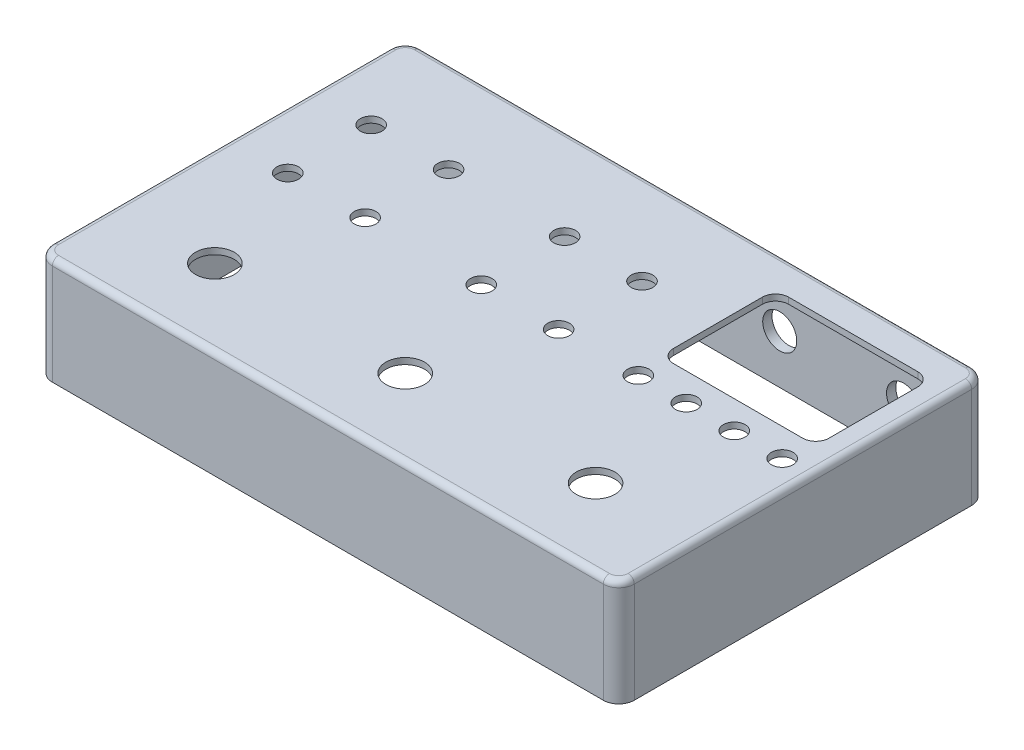
SolidWorks part; units mm, degrees
ref_plane "前视基准面" through (0, 0, 0) normal (0, 0, 1) x (1, 0, 0)
ref_plane "上视基准面" through (0, 0, 0) normal (0, 1, 0) x (1, 0, 0)
ref_plane "右视基准面" through (0, 0, 0) normal (1, 0, 0) x (0, 0, -1)
sketch "草图1" plane through (0, 0, 0) normal (0, 1, 0) x (1, 0, 0)
  line L0 (-67.19, 26.9473) -> (101.81, 26.9473) construction
  line L1 (-86.19, 56.9473) -> (101.81, 56.9473)
  line L2 (-86.19, 56.9473) -> (-86.19, -62.0527)
  line L3 (-86.19, -62.0527) -> (101.81, -62.0527)
  line L4 (101.81, 56.9473) -> (101.81, -62.0527)
  line L5 (-86.19, 26.9473) -> (-67.19, 26.9473) construction
  line L6 (-86.19, 0) -> (101.81, 0) construction
  line L7 (-86.19, -37.0527) -> (101.81, -37.0527) construction
  line L9 (48.445, 45.9473) -> (90.175, 45.9473)
  line L10 (44.445, 41.9473) -> (44.445, 13.2473)
  line L11 (48.445, 9.2473) -> (90.175, 9.2473)
  line L12 (94.175, 41.9473) -> (94.175, 13.2473)
  circle A0 centre (-67.19, 26.9473) radius 3.5
  circle A1 centre (-42.19, 26.9473) radius 3.5
  circle A2 centre (-67.19, 0) radius 3.5
  circle A3 centre (-42.19, 0) radius 3.5
  circle A4 centre (-4.69, 26.9473) radius 3.5
  circle A5 centre (20.31, 26.9473) radius 3.5
  circle A6 centre (-4.69, 0) radius 3.5
  circle A7 centre (20.31, 0) radius 3.5
  circle A8 centre (46.06, 0) radius 3.5
  circle A9 centre (61.56, 0) radius 3.5
  circle A10 centre (77.06, 0) radius 3.5
  circle A11 centre (92.56, 0) radius 3.5
  circle A12 centre (-53.69, -37.0527) radius 6.25
  circle A13 centre (7.81, -37.0527) radius 6.25
  circle A14 centre (69.31, -37.0527) radius 6.25
  arc A15 (90.175, 45.9473) -> (94.175, 41.9473) centre (90.175, 41.9473) cw
  arc A16 (48.445, 45.9473) -> (44.445, 41.9473) centre (48.445, 41.9473) ccw
  arc A17 (90.175, 9.2473) -> (94.175, 13.2473) centre (90.175, 13.2473) ccw
  arc A18 (44.445, 13.2473) -> (48.445, 9.2473) centre (48.445, 13.2473) ccw
  point P43 (69.31, 45.9473)
  point P49 (94.175, 45.9473)
  point P52 (44.445, 45.9473)
  point P55 (94.175, 9.2473)
  dimension "D3" = 30
  dimension "D12" = 7
  dimension "D16" = 12.5
  dimension "D19" = 49.73
  dimension "D23" = 4
  dimension "D1" = 188
  dimension "D2" = 119
  dimension "D4" = 19
  dimension "D5" = 25
  dimension "D6" = 25
  dimension "D7" = 37.5
  dimension "D8" = 9.25
  dimension "D9" = 15.5
  dimension "D10" = 15.5
  dimension "D11" = 15.5
  dimension "D13" = 32.5
  dimension "D14" = 61.5
  dimension "D15" = 61.5
  dimension "D17" = 25.75
  dimension "D18" = 19
  dimension "D20" = 36.7
  dimension "D21" = 11
  dimension "D22" = 25
extrude "凸台-拉伸1" add sketch "草图1" along normal blind 34.5
sketch "草图3" plane through (0, 0, 0) normal (0, -1, 0) x (1, 0, 0)
  line L1 (98.81, -53.9473) -> (-83.19, -53.9473)
  line L2 (98.81, -53.9473) -> (98.81, 59.0527)
  line L3 (98.81, 59.0527) -> (-83.19, 59.0527)
  line L4 (-86.19, 62.0527) -> (-86.19, -56.9473)
  line L5 (-86.19, -56.9473) -> (101.81, -56.9473)
  line L6 (101.81, -56.9473) -> (101.81, 62.0527)
  line L7 (101.81, 62.0527) -> (-86.19, 62.0527)
  line L8 (-86.19, 62.0527) -> (-86.19, -56.9473)
  line L9 (-86.19, -56.9473) -> (101.81, -56.9473)
  line L10 (101.81, -56.9473) -> (101.81, 62.0527)
  line L11 (101.81, 62.0527) -> (-86.19, 62.0527)
  line L12 (-83.19, -53.9473) -> (-83.19, 59.0527)
  dimension "D2" = 3
  dimension "D3" = 3
  dimension "D4" = 3
  dimension "D5" = 3
  dimension "D1" = 0
extrude "切除-拉伸2" cut sketch "草图3" against normal offset from surface (31.5 mm away) 3 up to face at (7.81, 34.5, 43.3027)
sketch "草图4" plane through (0, 34.5, 0) normal (0, 1, 0) x (1, 0, 0)
  line L0 (90.175, 45.9473) -> (48.445, 45.9473)
  line L1 (90.175, 45.9473) -> (48.445, 45.9473)
  line L2 (44.445, 41.9473) -> (44.445, 13.2473)
  line L3 (44.445, 41.9473) -> (44.445, 13.2473)
  line L4 (94.175, 13.2473) -> (94.175, 41.9473)
  line L5 (94.175, 13.2473) -> (94.175, 41.9473)
  line L6 (48.445, 9.2473) -> (90.175, 9.2473)
  line L7 (48.445, 9.2473) -> (90.175, 9.2473)
  arc A0 (48.445, 45.9473) -> (44.445, 41.9473) centre (48.445, 41.9473) ccw
  arc A1 (48.445, 45.9473) -> (44.445, 41.9473) centre (48.445, 41.9473) ccw
  arc A2 (44.445, 13.2473) -> (48.445, 9.2473) centre (48.445, 13.2473) ccw
  arc A3 (44.445, 13.2473) -> (48.445, 9.2473) centre (48.445, 13.2473) ccw
  arc A4 (94.175, 41.9473) -> (90.175, 45.9473) centre (90.175, 41.9473) ccw
  arc A5 (94.175, 41.9473) -> (90.175, 45.9473) centre (90.175, 41.9473) ccw
  arc A6 (90.175, 9.2473) -> (94.175, 13.2473) centre (90.175, 13.2473) ccw
  arc A7 (90.175, 9.2473) -> (94.175, 13.2473) centre (90.175, 13.2473) ccw
extrude "切除-拉伸-薄壁1" cut sketch "草图4" against normal blind 3 thin
fillet "圆角1" radius 5 8 edges at (-86.19, 17.25, -56.9473) (-86.19, 17.25, 62.0527) (-83.19, 15.75, 59.0527) (98.81, 15.75, -53.9473) (101.81, 17.25, -56.9473) (101.81, 17.25, 62.0527) (98.81, 15.75, 59.0527) (-83.19, 15.75, -53.9473)
sketch "草图5" plane through (0, 31.5, 0) normal (0, -1, 0) x (1, 0, 0)
  line L0 (93.81, 59.0527) -> (-78.19, 59.0527) construction
  line L1 (-80.69, -51.4473) -> (96.31, -51.4473)
  line L2 (-80.69, -51.4473) -> (-80.69, 56.5527)
  line L3 (-80.69, 56.5527) -> (96.31, 56.5527)
  line L4 (96.31, -51.4473) -> (96.31, 56.5527)
  line L5 (-83.19, -48.9473) -> (-83.19, 54.0527) construction
  line L6 (98.81, -48.9473) -> (98.81, 54.0527) construction
  line L7 (93.81, -53.9473) -> (-78.19, -53.9473) construction
  circle A0 centre (-80.69, -51.4473) radius 3.5
  circle A1 centre (-80.69, 56.5527) radius 3.5
  circle A2 centre (96.31, 56.5527) radius 3.5
  circle A3 centre (96.31, -51.4473) radius 3.5
  arc M34 (-78.19, 59.0527) -> (-83.19, 54.0527) centre (-78.19, 54.0527) ccw
  arc M36 (-83.19, -48.9473) -> (-78.19, -53.9473) centre (-78.19, -48.9473) ccw
  arc M38 (93.81, -53.9473) -> (98.81, -48.9473) centre (93.81, -48.9473) ccw
  arc M40 (98.81, 54.0527) -> (93.81, 59.0527) centre (93.81, 54.0527) ccw
  dimension "D1" = 2.5
  dimension "D5" = 7
  dimension "D2" = 2.5
  dimension "D3" = 2.5
  dimension "D4" = 2.5
extrude "凸台-拉伸2" add sketch "草图5" along normal up to surface (31.5 mm away) contours L3 A1 L2 M34 | L2 A1 L3 | A0 L1 L2 M36 | L1 A0 L2 | L3 A2 L4 | L4 A2 L3 M40 | L4 A3 L1 | A3 L4 L1 M38 up to face at (7.81, 0, 2.5527)
sketch "草图6" plane through (0, 0, 0) normal (0, -1, 0) x (1, 0, 0)
  circle A0 centre (96.31, -51.4473) radius 2.25
  circle A1 centre (96.31, 56.5527) radius 2.25
  circle A2 centre (-80.69, 56.5527) radius 2.25
  circle A3 centre (-80.69, -51.4473) radius 2.25
  dimension "D1" = 4.5
extrude "切除-拉伸3" cut sketch "草图6" against normal blind 20
fillet "圆角2" radius 2 8 edges at (-84.7255, 34.5, 60.5882) (-84.7255, 34.5, -55.4828) (100.3456, 34.5, -55.4828) (100.3456, 34.5, 60.5882) (101.81, 34.5, 2.5527) (7.81, 34.5, -56.9473) (-86.19, 34.5, 2.5527) (7.81, 34.5, 62.0527)
sketch "草图7" plane through (0, 0, -56.9473) normal (0, 0, -1) x (-1, 0, 0)
  line L0 (-96.81, 15.75) -> (81.19, 15.75) construction
  line L3 (-96.81, 32.5) -> (-96.81, 0) construction
  line L4 (81.19, 0) -> (81.19, 32.5) construction
  line L5 (-96.81, 34.5) -> (81.19, 34.5) construction
  line L8 (27.19, 19.25) -> (37.19, 19.25)
  line L9 (27.19, 19.25) -> (27.19, 12.25)
  line L10 (27.19, 12.25) -> (37.19, 12.25)
  line L11 (37.19, 19.25) -> (37.19, 12.25)
  line L12 (23.69, 17.5) -> (40.69, 17.5)
  line L13 (23.69, 17.5) -> (23.69, 14)
  line L14 (23.69, 14) -> (40.69, 14)
  line L15 (40.69, 17.5) -> (40.69, 14)
  circle A0 centre (-7.81, 15.75) radius 5.5
  circle A1 centre (62.19, 15.75) radius 5.5
  circle A3 centre (23.69, 15.75) radius 1.75
  circle A4 centre (40.69, 15.75) radius 1.75
  circle A5 centre (-37.81, 15.75) radius 5.5
  circle A6 centre (-77.81, 15.75) radius 5.5
  circle A7 centre (12.19, 15.75) radius 3
  point P14 (27.19, 15.75)
  point P21 (32.19, 19.25)
  point P22 (-7.81, 15.75)
  point P29 (32.19, 17.5)
  dimension "D2" = 30
  dimension "D5" = 11
  dimension "D6" = 11
  dimension "D7" = 3.5
  dimension "D3" = 3.5
  dimension "D11" = 11
  dimension "D14" = 6
  dimension "D1" = 18.75
  dimension "D4" = 17
  dimension "D8" = 3.5
  dimension "D9" = 7
  dimension "D10" = 40
  dimension "D12" = 30
  dimension "D13" = 40
  dimension "D15" = 20
  dimension "D16" = 10
extrude "切除-拉伸4" cut sketch "草图7" against normal blind 20 contours A1 L0 | A6 L0 | L0 A6 | A5 L0 | L0 A5 | A7 L0 | L8 L11 L10 L9 | A3 | A4
sketch "草图8" plane through (-86.19, 0, 0) normal (-1, 0, 0) x (0, 0, 1)
  line L0 (-56.9473, 0) -> (-56.9473, 32.5) construction
  line L1 (-51.9473, 34.5) -> (57.0527, 34.5) construction
  circle A0 centre (-31.9473, 15.75) radius 5
  dimension "D1" = 25
  dimension "D3" = 10
  dimension "D2" = 18.75
sketch "草图10" plane through (0, 31.5, 0) normal (0, -1, 0) x (1, 0, 0)
  line L4 (98.81, -48.9473) -> (98.81, 54.0527)
  line L5 (93.81, 59.0527) -> (-78.19, 59.0527)
  line L6 (-83.19, 54.0527) -> (-83.19, -48.9473)
  line L7 (-78.19, -53.9473) -> (93.81, -53.9473)
  line L8 (98.81, -48.9473) -> (98.81, 54.0527)
  line L9 (93.81, 59.0527) -> (-78.19, 59.0527)
  line L10 (-83.19, 54.0527) -> (-83.19, -48.9473)
  line L11 (-78.19, -53.9473) -> (93.81, -53.9473)
  arc A12 (98.8098, -48.9975) -> (93.8603, -53.947) centre (96.31, -51.4473) ccw
  arc A13 (98.8098, -48.9975) -> (98.81, -48.9473) centre (93.81, -48.9473) ccw
  arc A14 (98.81, 54.0527) -> (98.8098, 54.103) centre (93.81, 54.0527) ccw
  arc A15 (93.8603, 59.0525) -> (98.8098, 54.103) centre (96.31, 56.5527) ccw
  arc A16 (93.8603, 59.0525) -> (93.81, 59.0527) centre (93.81, 54.0527) ccw
  arc A17 (-78.19, 59.0527) -> (-78.2402, 59.0525) centre (-78.19, 54.0527) ccw
  arc A18 (-83.1897, 54.103) -> (-78.2402, 59.0525) centre (-80.69, 56.5527) ccw
  arc A19 (-83.1897, 54.103) -> (-83.19, 54.0527) centre (-78.19, 54.0527) ccw
  arc A20 (-83.19, -48.9473) -> (-83.1897, -48.9975) centre (-78.19, -48.9473) ccw
  arc A21 (-78.2402, -53.947) -> (-83.1897, -48.9975) centre (-80.69, -51.4473) ccw
  arc A22 (-78.2402, -53.947) -> (-78.19, -53.9473) centre (-78.19, -48.9473) ccw
  arc A23 (93.81, -53.9473) -> (93.8603, -53.947) centre (93.81, -48.9473) ccw
  arc A24 (98.8098, -48.9975) -> (93.8603, -53.947) centre (96.31, -51.4473) ccw
  arc A25 (98.8098, -48.9975) -> (98.81, -48.9473) centre (93.81, -48.9473) ccw
  arc A26 (98.81, 54.0527) -> (98.8098, 54.103) centre (93.81, 54.0527) ccw
  arc A27 (93.8603, 59.0525) -> (98.8098, 54.103) centre (96.31, 56.5527) ccw
  arc A28 (93.8603, 59.0525) -> (93.81, 59.0527) centre (93.81, 54.0527) ccw
  arc A29 (-78.19, 59.0527) -> (-78.2402, 59.0525) centre (-78.19, 54.0527) ccw
  arc A30 (-83.1897, 54.103) -> (-78.2402, 59.0525) centre (-80.69, 56.5527) ccw
  arc A31 (-83.1897, 54.103) -> (-83.19, 54.0527) centre (-78.19, 54.0527) ccw
  arc A32 (-83.19, -48.9473) -> (-83.1897, -48.9975) centre (-78.19, -48.9473) ccw
  arc A33 (-78.2402, -53.947) -> (-83.1897, -48.9975) centre (-80.69, -51.4473) ccw
  arc A34 (-78.2402, -53.947) -> (-78.19, -53.9473) centre (-78.19, -48.9473) ccw
  arc A35 (93.81, -53.9473) -> (93.8603, -53.947) centre (93.81, -48.9473) ccw
  dimension "D1" = 0
extrude "切除-拉伸5" cut sketch "草图10" against normal blind 1
sketch "草图9" plane through (0, 0, 0) normal (0, -1, 0) x (1, 0, 0)
  line L0 (-83.19, -48.9473) -> (-83.19, 54.0527) construction
  line L1 (93.81, 59.0527) -> (-78.19, 59.0527) construction
  line L2 (93.81, -53.9473) -> (-78.19, -53.9473) construction
  line L3 (98.81, -48.9473) -> (98.81, 54.0527) construction
  line L4 (-86.19, 57.0527) -> (-86.19, -51.9473)
  line L5 (-81.19, -56.9473) -> (96.81, -56.9473)
  line L6 (101.81, -51.9473) -> (101.81, 57.0527)
  line L7 (96.81, 62.0527) -> (-81.19, 62.0527)
  line L8 (-86.19, 57.0527) -> (-86.19, -51.9473)
  line L9 (-81.19, -56.9473) -> (96.81, -56.9473)
  line L10 (101.81, -51.9473) -> (101.81, 57.0527)
  line L11 (96.81, 62.0527) -> (-81.19, 62.0527)
  line L12 (-83.19, -48.9473) -> (-83.19, 54.0527)
  line L13 (93.81, 59.0527) -> (-78.19, 59.0527)
  line L14 (93.81, -53.9473) -> (-78.19, -53.9473)
  line L15 (98.81, -48.9473) -> (98.81, 54.0527)
  arc A0 (-78.2402, -53.947) -> (-83.1897, -48.9975) centre (-80.69, -51.4473) ccw construction
  arc A1 (-83.1897, 54.103) -> (-78.2402, 59.0525) centre (-80.69, 56.5527) ccw construction
  arc A2 (93.8603, 59.0525) -> (98.8098, 54.103) centre (96.31, 56.5527) ccw construction
  arc A3 (98.8098, -48.9975) -> (93.8603, -53.947) centre (96.31, -51.4473) ccw construction
  arc A4 (-86.19, -51.9473) -> (-81.19, -56.9473) centre (-81.19, -51.9473) ccw
  arc A5 (96.81, -56.9473) -> (101.81, -51.9473) centre (96.81, -51.9473) ccw
  arc A6 (101.81, 57.0527) -> (96.81, 62.0527) centre (96.81, 57.0527) ccw
  arc A7 (-81.19, 62.0527) -> (-86.19, 57.0527) centre (-81.19, 57.0527) ccw
  arc A8 (-86.19, -51.9473) -> (-81.19, -56.9473) centre (-81.19, -51.9473) ccw
  arc A9 (96.81, -56.9473) -> (101.81, -51.9473) centre (96.81, -51.9473) ccw
  arc A10 (101.81, 57.0527) -> (96.81, 62.0527) centre (96.81, 57.0527) ccw
  arc A11 (-81.19, 62.0527) -> (-86.19, 57.0527) centre (-81.19, 57.0527) ccw
  arc A12 (-78.2402, -53.947) -> (-83.1897, -48.9975) centre (-80.69, -51.4473) ccw
  arc A13 (-83.1897, 54.103) -> (-78.2402, 59.0525) centre (-80.69, 56.5527) ccw
  arc A14 (93.8603, 59.0525) -> (98.8098, 54.103) centre (96.31, 56.5527) ccw
  arc A15 (98.8098, -48.9975) -> (93.8603, -53.947) centre (96.31, -51.4473) ccw
  arc A16 (93.8603, 59.0525) -> (93.81, 59.0527) centre (93.81, 54.0527) ccw construction
  arc A17 (93.8603, 59.0525) -> (93.81, 59.0527) centre (93.81, 54.0527) ccw
  arc A18 (98.81, 54.0527) -> (98.8098, 54.103) centre (93.81, 54.0527) ccw construction
  arc A19 (98.81, 54.0527) -> (98.8098, 54.103) centre (93.81, 54.0527) ccw
  arc A20 (98.8098, -48.9975) -> (98.81, -48.9473) centre (93.81, -48.9473) ccw construction
  arc A21 (98.8098, -48.9975) -> (98.81, -48.9473) centre (93.81, -48.9473) ccw
  arc A22 (93.81, -53.9473) -> (93.8603, -53.947) centre (93.81, -48.9473) ccw construction
  arc A23 (93.81, -53.9473) -> (93.8603, -53.947) centre (93.81, -48.9473) ccw
  arc A24 (-83.19, -48.9473) -> (-83.1897, -48.9975) centre (-78.19, -48.9473) ccw construction
  arc A25 (-83.19, -48.9473) -> (-83.1897, -48.9975) centre (-78.19, -48.9473) ccw
  arc A26 (-78.2402, -53.947) -> (-78.19, -53.9473) centre (-78.19, -48.9473) ccw construction
  arc A27 (-78.2402, -53.947) -> (-78.19, -53.9473) centre (-78.19, -48.9473) ccw
  arc A28 (-83.1897, 54.103) -> (-83.19, 54.0527) centre (-78.19, 54.0527) ccw construction
  arc A29 (-83.1897, 54.103) -> (-83.19, 54.0527) centre (-78.19, 54.0527) ccw
  arc A30 (-78.19, 59.0527) -> (-78.2402, 59.0525) centre (-78.19, 54.0527) ccw construction
  arc A31 (-78.19, 59.0527) -> (-78.2402, 59.0525) centre (-78.19, 54.0527) ccw
  dimension "D1" = 0
